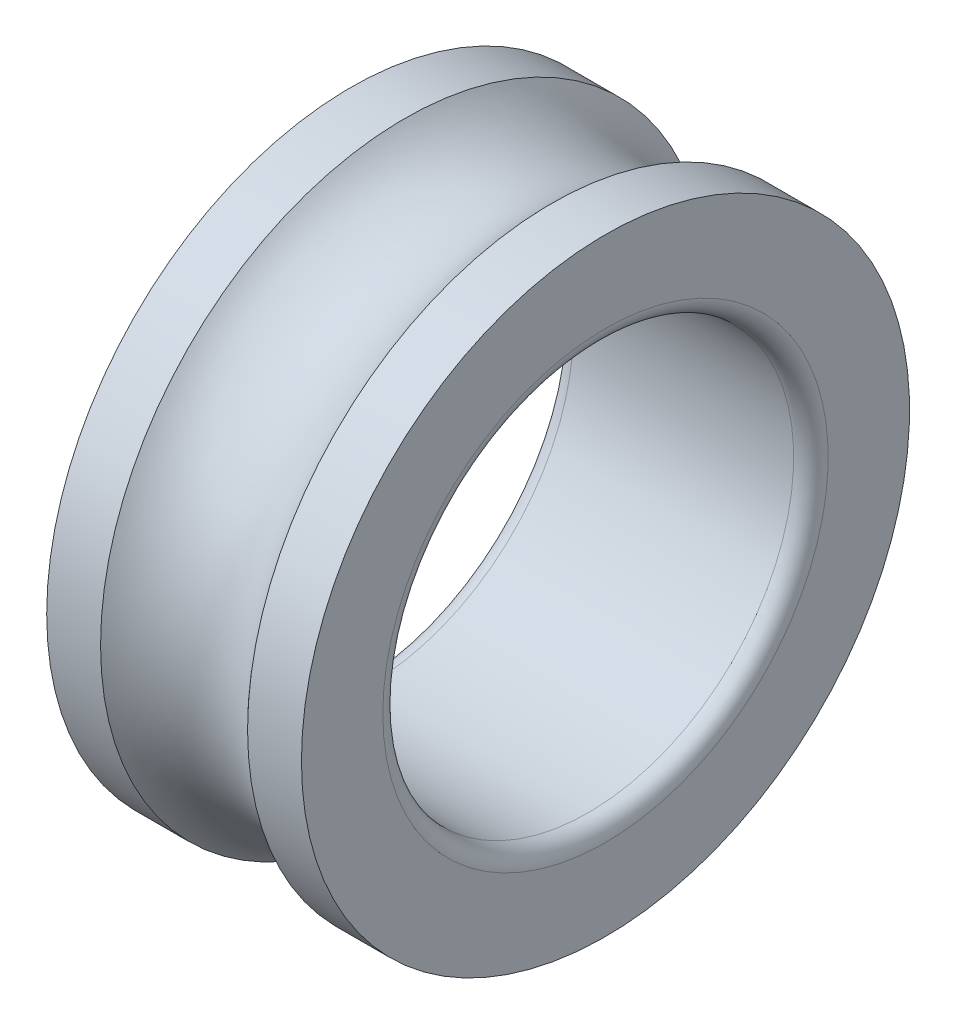
SolidWorks part; units mm, degrees
material "AISI 304"
ref_plane "Front" through (0, 0, 0) normal (0, 0, 1) x (1, 0, 0)
ref_plane "Top" through (0, 0, 0) normal (0, 1, 0) x (1, 0, 0)
ref_plane "Right" through (0, 0, 0) normal (1, 0, 0) x (0, 0, -1)
sketch "Sketch1" plane through (0, 0, 0) normal (0, 0, 1) x (1, 0, 0)
  line L0 (-11.1359, 0) -> (24.9053, 0) construction
  line L1 (8.9443, 37) -> (15.5, 37)
  line L2 (-15.5, 37) -> (-8.9443, 37)
  line L3 (-15.5, 37) -> (-15.5, 25)
  line L4 (-15.5, 25) -> (15.5, 25)
  line L5 (15.5, 37) -> (15.5, 25)
  line L6 (-15.5, 37) -> (15.5, 25) construction
  line L7 (-15.5, 25) -> (15.5, 37) construction
  line L8 (0, 25) -> (0, 0) construction
  arc A0 (8.9443, 37) -> (-8.9443, 37) centre (0, 45) cw
  point P3 (0, 31)
  dimension "D5" = 12
  dimension "D1" = 31
  dimension "D2" = 25
  dimension "D3" = 37
  dimension "D4" = 8
revolve "Revolve1" add sketch "Sketch1" angle 360 about L0
fillet "Fillet1" radius 2.1 2 edges at (-15.5, 0, 25) (15.5, 0, 25)
scale "Scale1" scale about centroid uniform scaling yes scale factor 0.1
